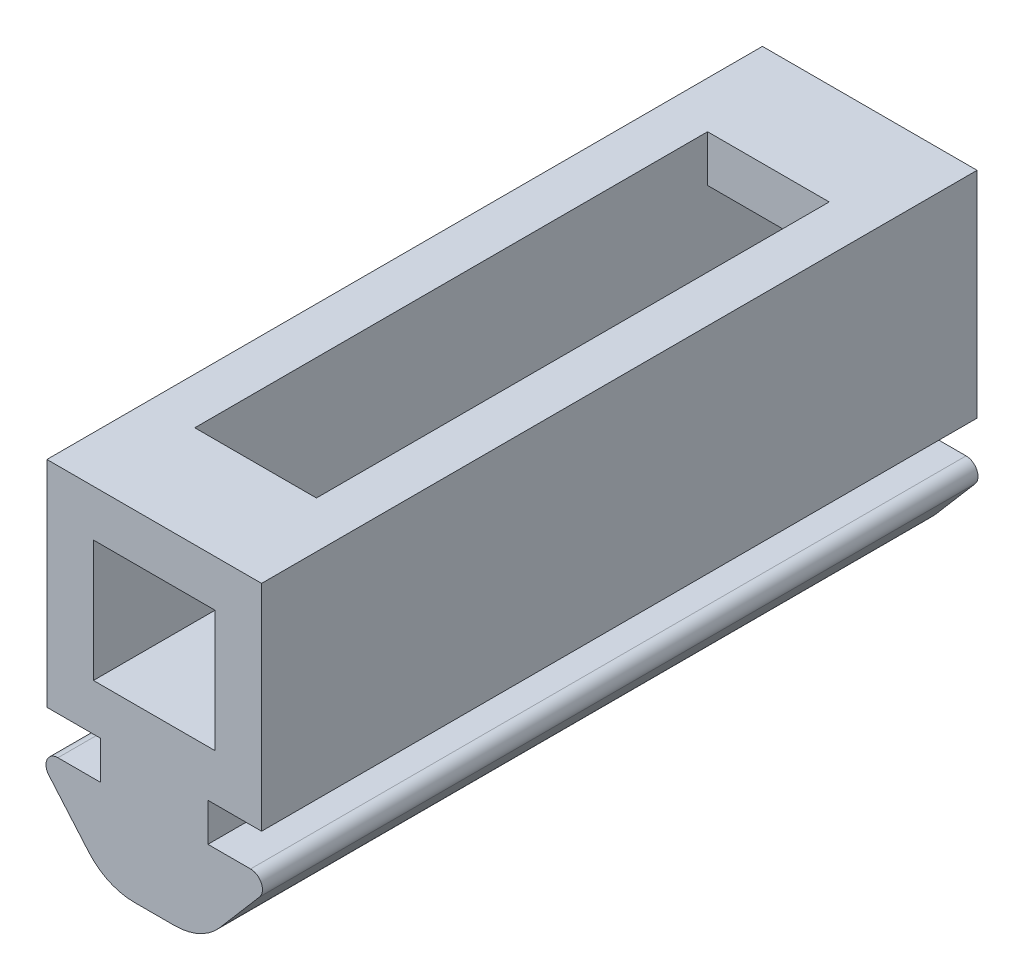
SolidWorks part; units mm, degrees
ref_plane "Front Plane" through (0, 0, 0) normal (0, 0, 1) x (1, 0, 0)
ref_plane "Top Plane" through (0, 0, 0) normal (0, 1, 0) x (1, 0, 0)
ref_plane "Right Plane" through (0, 0, 0) normal (1, 0, 0) x (0, 0, -1)
sketch "Sketch1" plane through (0, 0, 0) normal (0, 0, 1) x (1, 0, 0)
  line L0 (-4, 0) -> (4, 0)
  line L1 (4, 0) -> (10.25, 7.3)
  line L2 (10.25, 7.3) -> (4.5, 7.3)
  line L3 (4.5, 7.3) -> (4.5, 10.5)
  line L4 (4.5, 10.5) -> (-4.5, 10.5)
  line L5 (-4.5, 10.5) -> (-4.5, 7.3)
  line L6 (-4.5, 7.3) -> (-10.25, 7.3)
  line L7 (-10.25, 7.3) -> (-4, 0)
  line L9 (-9, 28.5) -> (9, 28.5)
  line L10 (-9, 28.5) -> (-9, 10.5)
  line L11 (-9, 10.5) -> (9, 10.5)
  line L12 (9, 28.5) -> (9, 10.5)
  line L13 (-9, 28.5) -> (9, 10.5) construction
  line L14 (-9, 10.5) -> (9, 28.5) construction
  line L15 (-5.1, 24.6) -> (5.1, 24.6)
  line L16 (-5.1, 24.6) -> (-5.1, 14.4)
  line L17 (-5.1, 14.4) -> (5.1, 14.4)
  line L18 (5.1, 24.6) -> (5.1, 14.4)
  line L19 (-5.1, 24.6) -> (5.1, 14.4) construction
  line L20 (-5.1, 14.4) -> (5.1, 24.6) construction
  point P0 (0, 10.5)
  point P3 (0, 19.5)
  point P4 (0, 0)
  point P18 (0, 19.5)
  dimension "D1" = 8
  dimension "D2" = 20.5
  dimension "D3" = 9
  dimension "D4" = 3.2
  dimension "D5" = 10.5
  dimension "D6" = 18
  dimension "D7" = 10.2
extrude "Boss-Extrude3" add sketch "Sketch1" along normal blind 60 contours L12 L9 L10 L11 L4 L15 L18 L17 L16 | L6 L7 L0 L1 L2 L3 L4 L5
fillet "Fillet1" radius 1 2 edges at (10.25, 7.3, 30) (-10.25, 7.3, 30)
fillet "Fillet2" radius 5 2 edges at (4, 0, 30) (-4, 0, 30)
sketch "Sketch2" plane through (0, 28.5, 0) normal (0, 1, 0) x (1, 0, 0)
  line L0 (9, -60) -> (9, 0) construction
  line L1 (-5.1, -8.5) -> (5.1, -8.5)
  line L2 (-5.1, -8.5) -> (-5.1, -51.5)
  line L3 (-5.1, -51.5) -> (5.1, -51.5)
  line L4 (5.1, -8.5) -> (5.1, -51.5)
  line L5 (-5.1, -8.5) -> (5.1, -51.5) construction
  line L6 (-5.1, -51.5) -> (5.1, -8.5) construction
  point P0 (0, -30)
  point P8 (9, -30)
  dimension "D1" = 43
  dimension "D2" = 10.2
extrude "Cut-Extrude1" cut sketch "Sketch2" against normal blind 10
